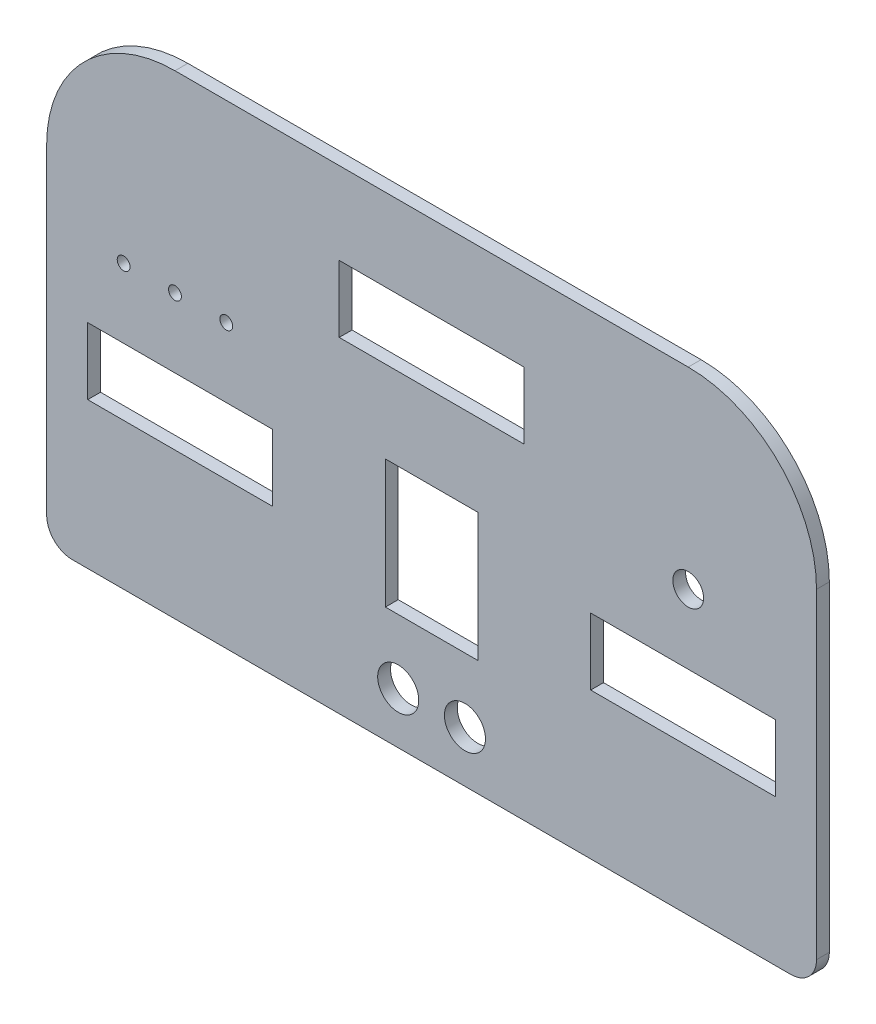
SolidWorks part; units mm, degrees
ref_plane "Front Plane" through (0, 0, 0) normal (0, 0, 1) x (1, 0, 0)
ref_plane "Top Plane" through (0, 0, 0) normal (0, 1, 0) x (1, 0, 0)
ref_plane "Right Plane" through (0, 0, 0) normal (1, 0, 0) x (0, 0, -1)
sketch "Sketch1" plane through (0, 0, 0) normal (0, 0, 1) x (1, 0, 0)
  line L0 (0, 162.6011) -> (0, -151.0749) construction
  line L1 (140, -92.5) -> (-140, -92.5)
  line L2 (150, -82.5) -> (150, 42.5)
  line L3 (100, 92.5) -> (-100, 92.5)
  line L4 (-150, -82.5) -> (-150, 42.5)
  line L5 (150, -92.5) -> (-150, 92.5) construction
  line L6 (150, 92.5) -> (-150, -92.5) construction
  line L8 (-134, -9.5) -> (-62, -9.5)
  line L9 (-134, -9.5) -> (-134, -35.5)
  line L10 (-134, -35.5) -> (-62, -35.5)
  line L11 (-62, -9.5) -> (-62, -35.5)
  line L12 (-134, -9.5) -> (-62, -35.5) construction
  line L13 (-134, -35.5) -> (-62, -9.5) construction
  line L14 (36, 34.5) -> (-36, 34.5)
  line L15 (36, 34.5) -> (36, 60.5)
  line L16 (36, 60.5) -> (-36, 60.5)
  line L17 (-36, 34.5) -> (-36, 60.5)
  line L18 (36, 34.5) -> (-36, 60.5) construction
  line L19 (36, 60.5) -> (-36, 34.5) construction
  line L20 (134, -35.5) -> (62, -35.5)
  line L21 (134, -35.5) -> (134, -9.5)
  line L22 (134, -9.5) -> (62, -9.5)
  line L23 (62, -35.5) -> (62, -9.5)
  line L24 (134, -35.5) -> (62, -9.5) construction
  line L25 (134, -9.5) -> (62, -35.5) construction
  line L26 (18, -47.5) -> (-18, -47.5)
  line L27 (18, -47.5) -> (18, 2.5)
  line L28 (18, 2.5) -> (-18, 2.5)
  line L29 (-18, -47.5) -> (-18, 2.5)
  line L30 (18, -47.5) -> (-18, 2.5) construction
  line L31 (18, 2.5) -> (-18, -47.5) construction
  arc A0 (150, -82.5) -> (140, -92.5) centre (140, -82.5) cw
  arc A1 (-140, -92.5) -> (-150, -82.5) centre (-140, -82.5) cw
  arc A2 (-150, 42.5) -> (-100, 92.5) centre (-100, 42.5) cw
  arc A3 (100, 92.5) -> (150, 42.5) centre (100, 42.5) cw
  circle A5 centre (-13, -72.5) radius 8
  circle A6 centre (13, -72.5) radius 8
  circle A7 centre (100, 17.5) radius 6
  circle A8 centre (-120, 17.5) radius 2.5
  circle A9 centre (-100, 17.5) radius 2.5
  circle A10 centre (-80, 17.5) radius 2.5
  point P0 (0, 0)
  point P20 (-98, -22.5)
  point P25 (0, 47.5)
  point P30 (98, -22.5)
  point P36 (0, -22.5)
  point P52 (0, 0)
  point P53 (0, 0)
  point P54 (0, 0)
  point P55 (0, 0)
  point P56 (0, 0)
  dimension "D3" = 10
  dimension "D4" = 50
  dimension "D5" = 50
  dimension "D18" = 16
  dimension "D19" = 13
  dimension "D21" = 12
  dimension "D22" = 5
  dimension "D23" = 5
  dimension "D24" = 5
  dimension "D1" = 185
  dimension "D2" = 300
  dimension "D6" = 72
  dimension "D7" = 26
  dimension "D8" = 88
  dimension "D9" = 70
  dimension "D10" = 88
  dimension "D11" = 72
  dimension "D12" = 72
  dimension "D13" = 26
  dimension "D14" = 26
  dimension "D15" = 45
  dimension "D16" = 50
  dimension "D17" = 36
  dimension "D20" = 20
  dimension "D25" = 20
  dimension "D26" = 20
  dimension "D27" = 75
  dimension "D28" = 50
extrude "Boss-Extrude1" add sketch "Sketch1" along normal blind 5
